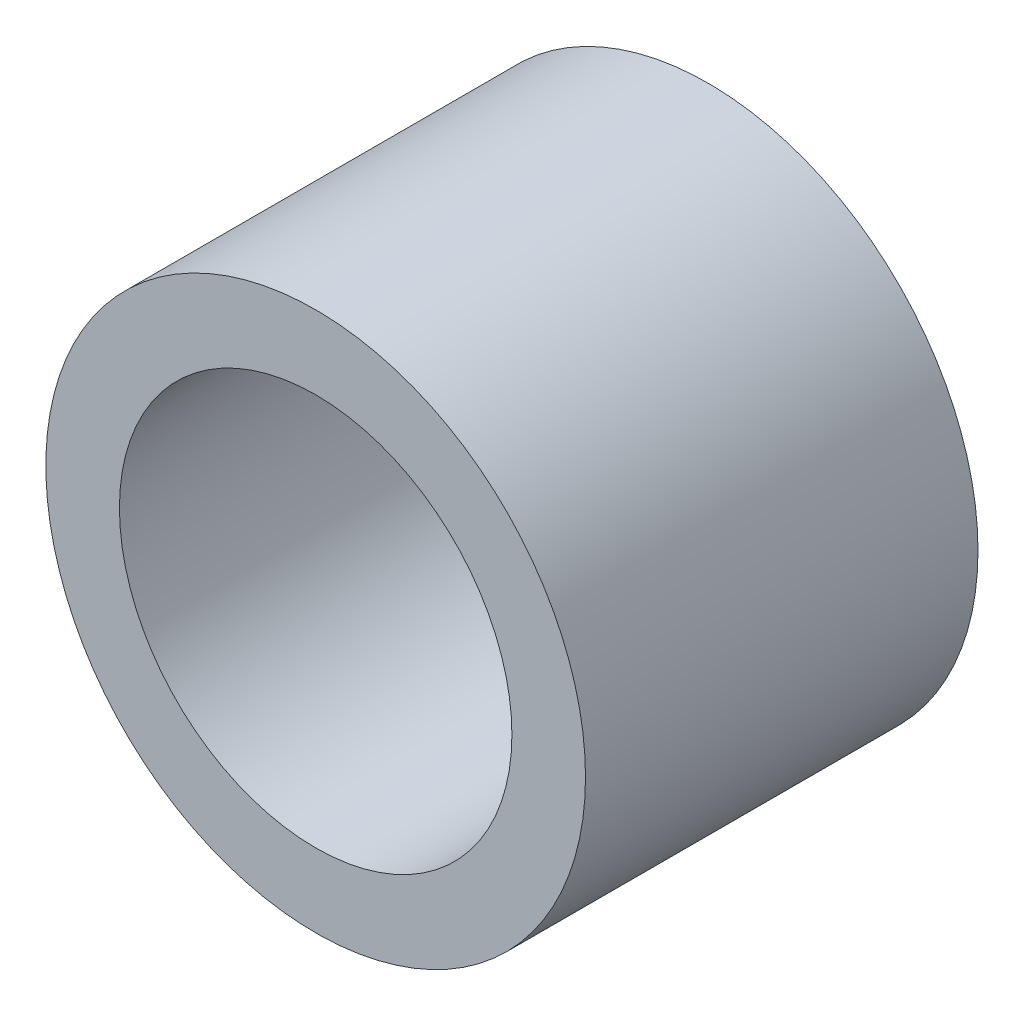
SolidWorks part; units mm, degrees
ref_plane "Front Plane" through (0, 0, 0) normal (0, 0, 1) x (1, 0, 0)
ref_plane "Top Plane" through (0, 0, 0) normal (0, 1, 0) x (1, 0, 0)
ref_plane "Right Plane" through (0, 0, 0) normal (1, 0, 0) x (0, 0, -1)
sketch "Sketch1" plane through (0, 0, 0) normal (0, 0, 1) x (1, 0, 0)
  circle A0 centre (0, 0) radius 4
  circle A1 centre (0, 0) radius 5.5
  dimension "D1" = 8
  dimension "D2" = 11
extrude "Boss-Extrude1" add sketch "Sketch1" along normal blind 8
